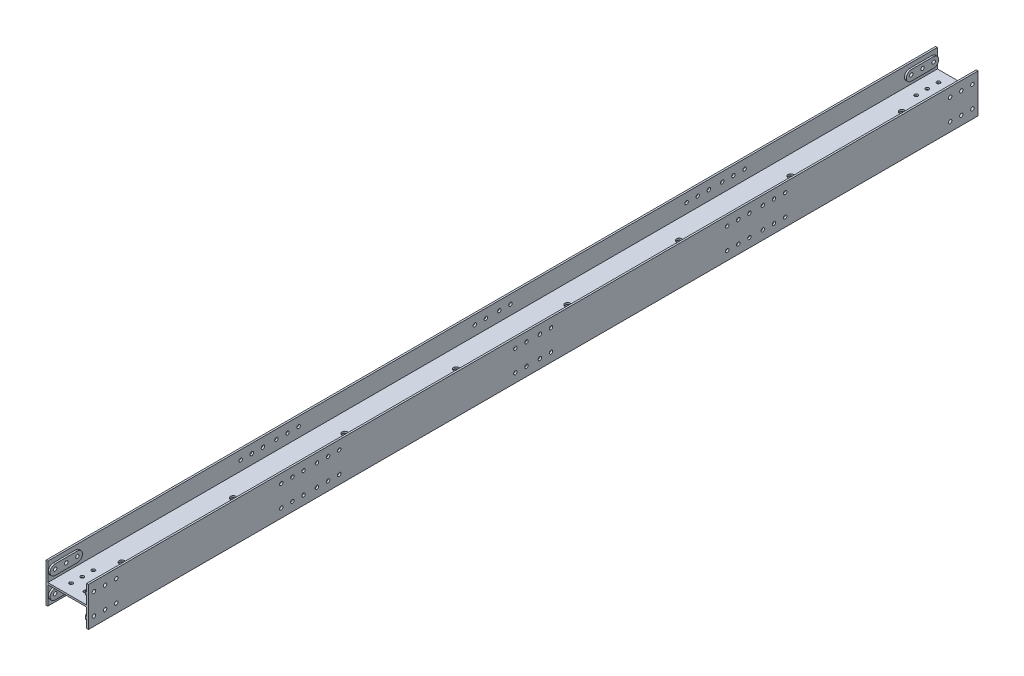
SolidWorks part; units mm, degrees
ref_plane "前视基准面" through (0, 0, 0) normal (0, 0, 1) x (1, 0, 0)
ref_plane "上视基准面" through (0, 0, 0) normal (0, 1, 0) x (1, 0, 0)
ref_plane "右视基准面" through (0, 0, 0) normal (1, 0, 0) x (0, 0, -1)
sketch "草图1" plane through (0, 0, 0) normal (0, 0, 1) x (1, 0, 0)
  line L0 (-1000, 0) -> (49000, 0) construction
  line L1 (0, -1000) -> (0, 49000) construction
  line L3 (-190, 175) -> (190, 175)
  line L4 (-190, 175) -> (-190, -175)
  line L5 (-190, -175) -> (190, -175)
  line L6 (190, 175) -> (190, -175)
  line L7 (-174, 175) -> (174, 175)
  line L8 (-174, 175) -> (-174, 8)
  line L9 (-174, 8) -> (174, 8)
  line L10 (174, 175) -> (174, 8)
  line L11 (-174, -8) -> (174, -8)
  line L12 (-174, -8) -> (-174, -175)
  line L13 (-174, -175) -> (174, -175)
  line L14 (174, -8) -> (174, -175)
  dimension "D1" = 380
  dimension "D2" = 350
  dimension "D3" = 190
  dimension "D4" = 175
  dimension "D5" = 8
  dimension "D6" = 16
  dimension "D7" = 16
  dimension "D8" = 16
extrude "拉伸1" add sketch "草图1" along normal blind 3990 contours L11 L14 L5 L6 L3 L10 L9 L8 L4 L12
sketch "草图2" plane through (190, 0, 0) normal (1, 0, 0) x (0, 0, -1)
  line L0 (-4990, 0) -> (45010, 0) construction
  line L1 (-3990, 175) -> (-3990, -175) construction
  line L2 (-3940, 95) -> (-3840, 95) construction
  line L3 (-3940, 95) -> (-3940, -95) construction
  line L4 (-3940, 95) -> (-2260, 95) construction
  line L5 (-2060, 95) -> (-1740, 95) construction
  circle A0 centre (-3940, 95) radius 15.5
  circle A1 centre (-3840, 95) radius 15.5
  circle A2 centre (-3740, 95) radius 15.5
  circle A3 centre (-3940, -95) radius 15.5
  circle A4 centre (-3840, -95) radius 15.5
  circle A5 centre (-3740, -95) radius 15.5
  circle A6 centre (-2260, 95) radius 15.5
  circle A7 centre (-2160, 95) radius 15.5
  circle A8 centre (-2060, 95) radius 15.5
  circle A9 centre (-2260, -95) radius 15.5
  circle A10 centre (-2160, -95) radius 15.5
  circle A11 centre (-2060, -95) radius 15.5
  circle A12 centre (-1740, 95) radius 15.5
  circle A13 centre (-1940, 95) radius 15.5
  circle A14 centre (-1840, 95) radius 15.5
  circle A15 centre (-1940, -95) radius 15.5
  circle A16 centre (-1840, -95) radius 15.5
  circle A17 centre (-1740, -95) radius 15.5
  circle A19 centre (-60, 95) radius 15.5
  circle A20 centre (-60, -95) radius 15.5
  circle A21 centre (-160, 95) radius 15.5
  circle A22 centre (-160, -95) radius 15.5
  circle A24 centre (-260, 95) radius 15.5 [skipped]
  circle A25 centre (-260, -95) radius 15.5 [skipped]
  point P5 (-3990, 0)
  dimension "D1" = 31
  dimension "D2" = 50
  dimension "D3" = 95
  dimension "D4" = 100
  dimension "D5" = 100
  dimension "D6" = 190
  dimension "D7" = 1680
  dimension "D8" = 320
  dimension "D9" = 1580
sketch "草图3" plane through (-174, 0, 0) normal (1, 0, 0) x (0, 0, -1)
  line L0 (-4990, 91.5) -> (45010, 91.5) construction
  line L1 (-3990, 175) -> (-3990, 8) construction
  line L2 (-3940, 91.5) -> (-3740, 91.5) construction
  line L3 (-3940, 136.801) -> (-3740, 136.801)
  line L4 (-3940, 46.199) -> (-3740, 46.199)
  arc A0 (-3940, 136.801) -> (-3940, 46.199) centre (-3940, 91.5) ccw
  arc A1 (-3740, 46.199) -> (-3740, 136.801) centre (-3740, 91.5) ccw
  point P5 (-3990, 91.5)
  point P7 (-3840, 91.5)
  dimension "D1" = 90.6019
  dimension "D2" = 200
  dimension "D3" = 50
extrude "拉伸2" add sketch "草图3" along normal blind 16
pattern_linear "阵列(线性)1" count 2 spacing 332 along (1, 0, 0) of "拉伸2"
pattern_linear "阵列(线性)2" count 2 spacing 190 along (0, -1, 0) of "拉伸2", "阵列(线性)1"
extrude "拉伸3" cut sketch "草图2" against normal through all
mirror "镜向1" about plane through (0, 0, 0) normal (0, 0, 1) of bodies 106
sketch "草图4" plane through (0, 8, 0) normal (0, 1, 0) x (1, 0, 0)
  line L0 (0, 2990) -> (0, 52990) construction
  line L1 (-174, 3990) -> (174, 3990) construction
  line L2 (-1174, 0) -> (48826, 0) construction
  line L3 (-174, -3990) -> (-174, 3990) construction
  line L4 (0, -2990) -> (0, -52990) construction
  circle A0 centre (65, 3890) radius 15.5
  circle A1 centre (-65, 3890) radius 15.5
  circle A2 centre (-65, 3790) radius 15.5
  circle A3 centre (65, 3790) radius 15.5
  circle A4 centre (-65, 3690) radius 15.5
  circle A5 centre (65, 3690) radius 15.5
  circle A6 centre (0, 3500) radius 25
  circle A7 centre (0, 2500) radius 25
  circle A8 centre (0, 1500) radius 25
  circle A9 centre (0, 500) radius 25
  circle A10 centre (0, -500) radius 25
  circle A11 centre (0, -1500) radius 25
  circle A12 centre (0, -2500) radius 25
  circle A13 centre (0, -3500) radius 25
  circle A14 centre (-65, -3790) radius 15.5
  circle A15 centre (-65, -3690) radius 15.5
  circle A16 centre (65, -3690) radius 15.5
  circle A17 centre (65, -3790) radius 15.5
  circle A18 centre (65, -3890) radius 15.5
  circle A19 centre (-65, -3890) radius 15.5
  point P5 (0, 3990)
  point P30 (-174, 0)
  dimension "D1" = 31
  dimension "D6" = 50
  dimension "D8" = 500
  dimension "D2" = 100
  dimension "D3" = 65
  dimension "D4" = 100
  dimension "D5" = 130
  dimension "D7" = 190
extrude "拉伸4" cut sketch "草图4" against normal through all
